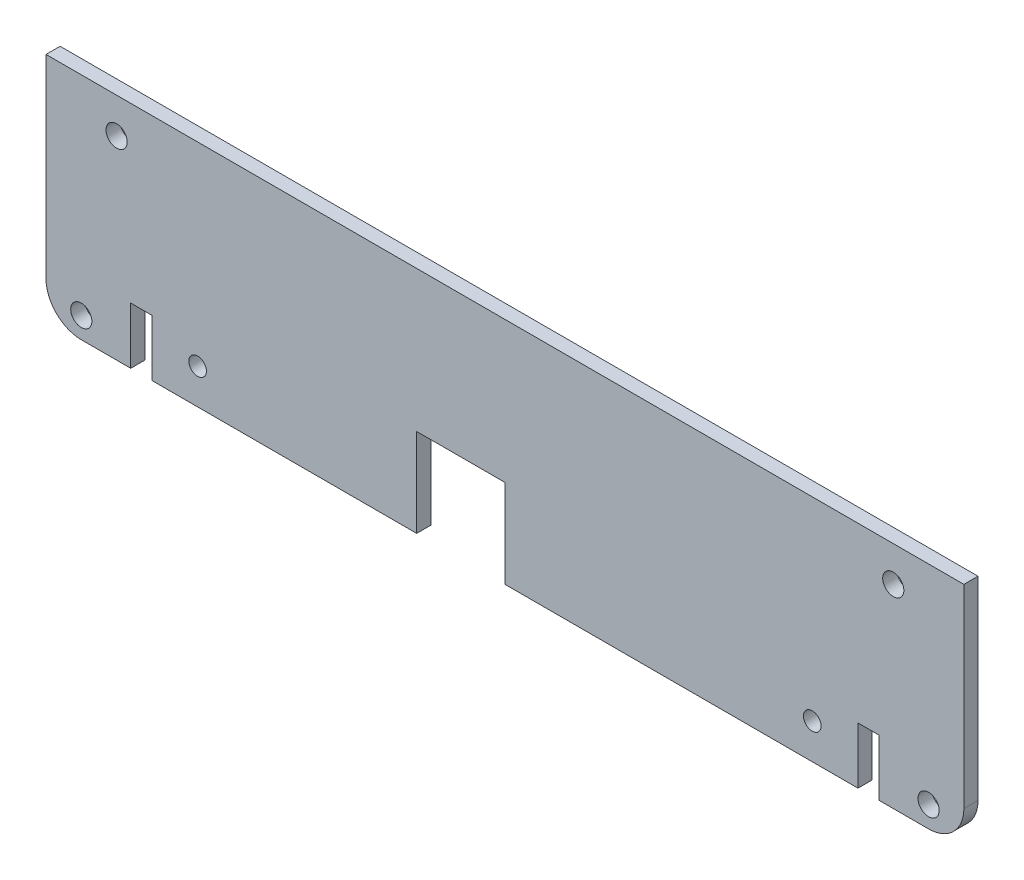
SolidWorks part; units mm, degrees
ref_plane "Front Plane" through (0, 0, 0) normal (0, 0, 1) x (1, 0, 0)
ref_plane "Top Plane" through (0, 0, 0) normal (0, 1, 0) x (1, 0, 0)
ref_plane "Right Plane" through (0, 0, 0) normal (1, 0, 0) x (0, 0, -1)
sketch "Sketch1" plane through (0, 0, 0) normal (0, 0, 1) x (1, 0, 0)
  line L1 (-130, 32.5) -> (130, 32.5)
  line L2 (-130, 32.5) -> (-130, -32.5)
  line L3 (-130, -32.5) -> (130, -32.5)
  line L4 (130, 32.5) -> (130, -32.5)
  line L5 (-130, 32.5) -> (130, -32.5) construction
  line L6 (-130, -32.5) -> (130, 32.5) construction
  point P0 (0, 0)
  dimension "D1" = 65
  dimension "D2" = 260
extrude "Boss-Extrude2" add sketch "Sketch1" along normal blind 4
sketch "Sketch3" plane through (0, 0, 0) normal (0, 0, -1) x (-1, 0, 0)
  circle A1 centre (120, -26.5) radius 3 construction
  circle A2 centre (-120, -26.5) radius 3 construction
  circle A4 centre (120, -26.5) radius 3
  circle A5 centre (-110, 22.5) radius 3 construction
  circle A6 centre (110, 22.5) radius 3 construction
  circle A7 centre (-120, -26.5) radius 3
  circle A8 centre (-110, 22.5) radius 3
  circle A9 centre (110, 22.5) radius 3
extrude "Cut-Extrude2" cut sketch "Sketch3" against normal through all
fillet "Fillet1" radius 10 2 edges at (-130, -32.5, 2) (130, -32.5, 2)
sketch "Sketch4" plane through (0, 0, 0) normal (0, 0, -1) x (-1, 0, 0)
  line L2 (120, -32.5) -> (-120, -32.5) construction
  line L3 (0, -32.5) -> (25, -32.5)
  line L4 (0, -32.5) -> (0, -7.5)
  line L6 (0, -7.5) -> (25, -7.5)
  line L7 (25, -32.5) -> (25, -7.5)
  dimension "D1" = 25
  dimension "D2" = 25
extrude "Cut-Extrude3" cut sketch "Sketch4" against normal blind 10
sketch "Sketch5" plane through (0, 0, 0) normal (0, 0, -1) x (-1, 0, 0)
  line L0 (0, -32.5) -> (-120, -32.5) construction
  line L1 (-106, -32.5) -> (-100, -32.5)
  line L2 (-106, -32.5) -> (-106, -16.5)
  line L3 (-106, -16.5) -> (-100, -16.5)
  line L4 (-100, -32.5) -> (-100, -16.5)
  line L5 (-130, -22.5) -> (-130, 32.5) construction
  line L6 (0, 0) -> (0, 32.5) construction
  line L7 (-130, 32.5) -> (130, 32.5) construction
  line L8 (100, -32.5) -> (100, -16.5)
  line L9 (106, -16.5) -> (100, -16.5)
  line L10 (106, -32.5) -> (106, -16.5)
  line L11 (106, -32.5) -> (100, -32.5)
  dimension "D1" = 24
  dimension "D2" = 6
  dimension "D3" = 16
extrude "Cut-Extrude4" cut sketch "Sketch5" against normal through all
sketch "Sketch6" plane through (0, 0, 0) normal (0, 0, -1) x (-1, 0, 0)
  circle A0 centre (87.05, -22.5) radius 2.5 construction
  circle A1 centre (-87.05, -22.5) radius 2.5 construction
  circle A2 centre (87.05, -22.5) radius 2.5
  circle A3 centre (-87.05, -22.5) radius 2.5
extrude "Cut-Extrude5" cut sketch "Sketch6" against normal through all
